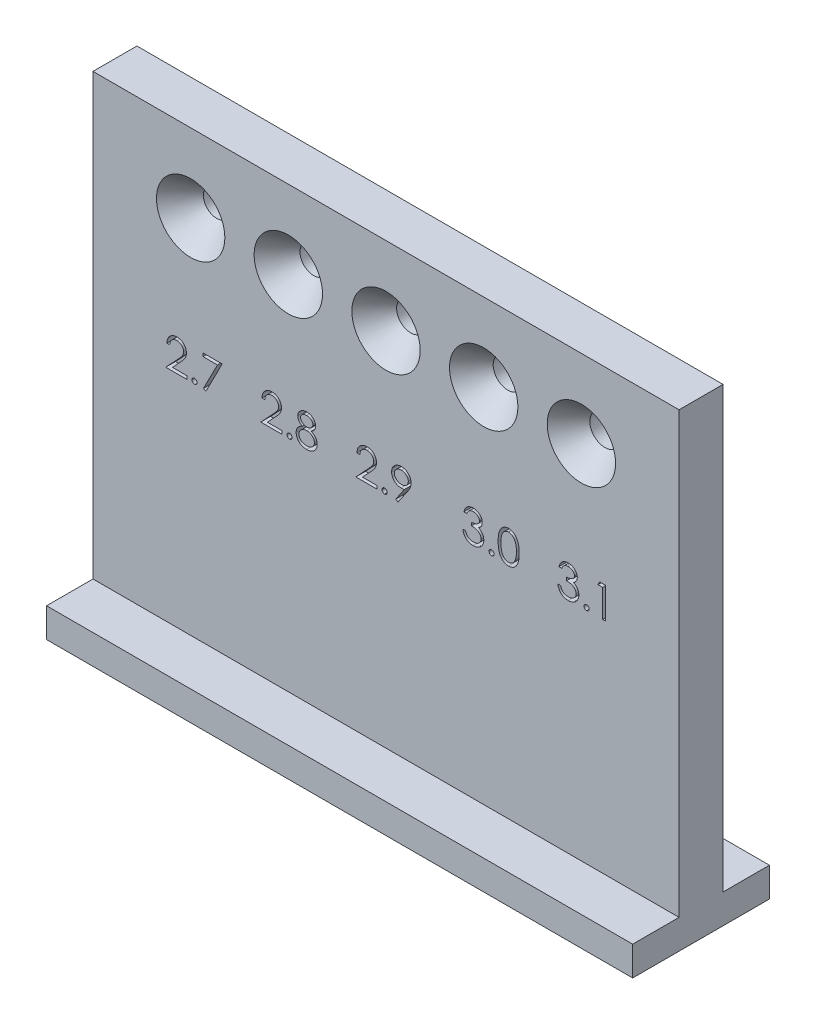
SolidWorks part; units mm, degrees
ref_plane "Front Plane" through (0, 0, 0) normal (0, 0, 1) x (1, 0, 0)
ref_plane "Top Plane" through (0, 0, 0) normal (0, 1, 0) x (1, 0, 0)
ref_plane "Right Plane" through (0, 0, 0) normal (1, 0, 0) x (0, 0, -1)
sketch "Sketch1" plane through (0, 0, 0) normal (0, 1, 0) x (1, 0, 0)
  line L1 (-30, 7) -> (30, 7)
  line L2 (-30, 7) -> (-30, -7)
  line L3 (-30, -7) -> (30, -7)
  line L4 (30, 7) -> (30, -7)
  line L5 (-30, 7) -> (30, -7) construction
  line L6 (-30, -7) -> (30, 7) construction
  point P0 (0, 0)
  dimension "D1" = 60
  dimension "D2" = 14
extrude "Boss-Extrude1" add sketch "Sketch1" along normal blind 3
sketch "Sketch2" plane through (0, 3, 0) normal (0, 1, 0) x (1, 0, 0)
  line L0 (30, -7) -> (30, 7) construction
  line L1 (-30, -2.25) -> (30, -2.25)
  line L2 (-30, -2.25) -> (-30, 2.25)
  line L3 (-30, 2.25) -> (30, 2.25)
  line L4 (30, -2.25) -> (30, 2.25)
  line L5 (-30, -2.25) -> (30, 2.25) construction
  line L6 (-30, 2.25) -> (30, -2.25) construction
  point P0 (0, 0)
  dimension "D1" = 4.5
extrude "Boss-Extrude2" add sketch "Sketch2" along normal blind 45
sketch "Sketch3" plane through (0, 0, 2.25) normal (0, 0, 1) x (1, 0, 0)
  line L0 (-30, 40) -> (30, 40) construction
  line L1 (-30, 48) -> (-30, 3) construction
  line L2 (30, 48) -> (30, 3) construction
  line L3 (-30, 48) -> (30, 48) construction
  circle A0 centre (-20, 40) radius 1.35
  circle A1 centre (-10, 40) radius 1.4
  circle A2 centre (0, 40) radius 1.45
  circle A3 centre (10, 40) radius 1.5
  circle A4 centre (20, 40) radius 1.55
  dimension "D2" = 2.7
  dimension "D3" = 2.8
  dimension "D4" = 2.9
  dimension "D5" = 3
  dimension "D6" = 3.1
  dimension "D1" = 8
  dimension "D7" = 60
  dimension "D8" = 10
  dimension "D9" = 10
  dimension "D10" = 10
  dimension "D11" = 10
  dimension "D12" = 10
extrude "Cut-Extrude1" cut sketch "Sketch3" against normal up to next
sketch "Sketch4" plane through (0, 0, 2.25) normal (0, 0, 1) x (1, 0, 0)
  circle A0 centre (-20, 40) radius 3.5
  circle A1 centre (-10, 40) radius 3.5
  circle A2 centre (0, 40) radius 3.5
  circle A3 centre (10, 40) radius 3.5
  circle A4 centre (20, 40) radius 3.5
  dimension "D1" = 7
  dimension "D3" = 10
  dimension "D2" = 5
extrude "Cut-Extrude2" cut sketch "Sketch4" against normal blind 2.7 draft 39
sketch "Sketch5" plane through (0, 0, 2.25) normal (0, 0, 1) x (1, 0, 0)
  line L0 (-30, 25.5) -> (30, 25.5) construction
  line L1 (-30, 48) -> (-30, 3) construction
  line L2 (30, 48) -> (30, 3) construction
  text T0 "      2.7   2.8   2.9    3.0   3.1"
extrude "Cut-Extrude3" cut sketch "Sketch5" against normal blind 1
equation "\"D9@Sketch3\"=\"D8@Sketch3\""
equation "\"D10@Sketch3\"=\"D8@Sketch3\""
equation "\"D11@Sketch3\"=\"D8@Sketch3\""
equation "\"D12@Sketch3\"=\"D8@Sketch3\""
